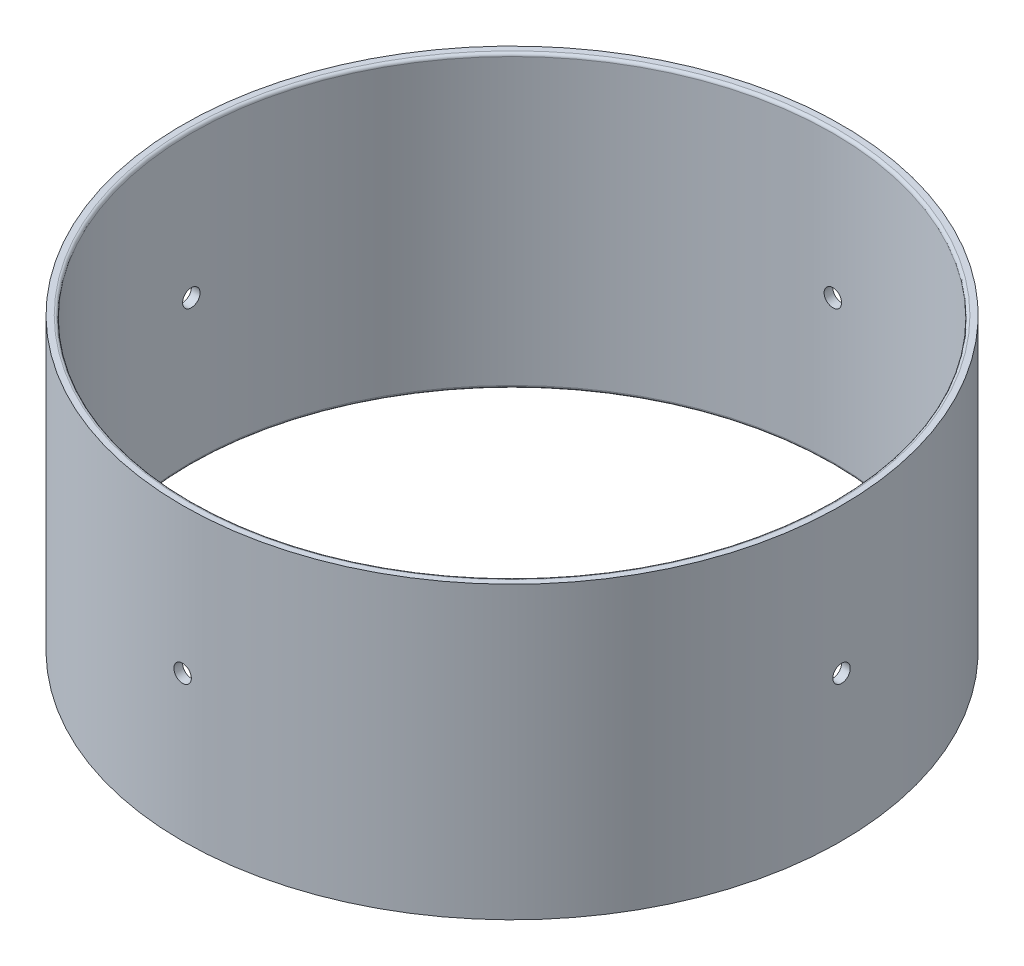
SolidWorks part; units mm, degrees
ref_plane "Front Plane" through (0, 0, 0) normal (0, 0, 1) x (1, 0, 0)
ref_plane "Top Plane" through (0, 0, 0) normal (0, 1, 0) x (1, 0, 0)
ref_plane "Right Plane" through (0, 0, 0) normal (1, 0, 0) x (0, 0, -1)
sketch "Sketch1" plane through (0, 0, 0) normal (0, 1, 0) x (1, 0, 0)
  circle A0 centre (0, 0) radius 55.2
  circle A1 centre (0, 0) radius 56.7
  dimension "D1" = 110.4
  dimension "D2" = 1.5
extrude "Boss-Extrude1" add sketch "Sketch1" along normal blind 50
fillet "Fillet1" radius 0.5 2 edges at (0, 50, 55.2) (0, 0, 55.2)
ref_plane "Plane1" through (56.7, 0, 0) normal (1, 0, 0) x (0, 0, -1)
sketch "Sketch2" plane through (56.7, 0, 0) normal (1, 0, 0) x (0, 0, -1)
  line L0 (0, 50) -> (0, 0) construction
  line L1 (55.7, 50) -> (-55.7, 50) construction
  line L2 (-56.7, 0) -> (56.7, 0) construction
  circle A0 centre (0, 25) radius 1.5
  dimension "D1" = 3
extrude "Cut-Extrude1" cut sketch "Sketch2" against normal blind 10
ref_axis "Axis1" through (0, 48.0635, 0) along (0, -1, 0)
pattern_circular "CirPattern1" count 4 over 360 about axis through (0, 48.0635, 0) along (0, -1, 0) of "Cut-Extrude1"
